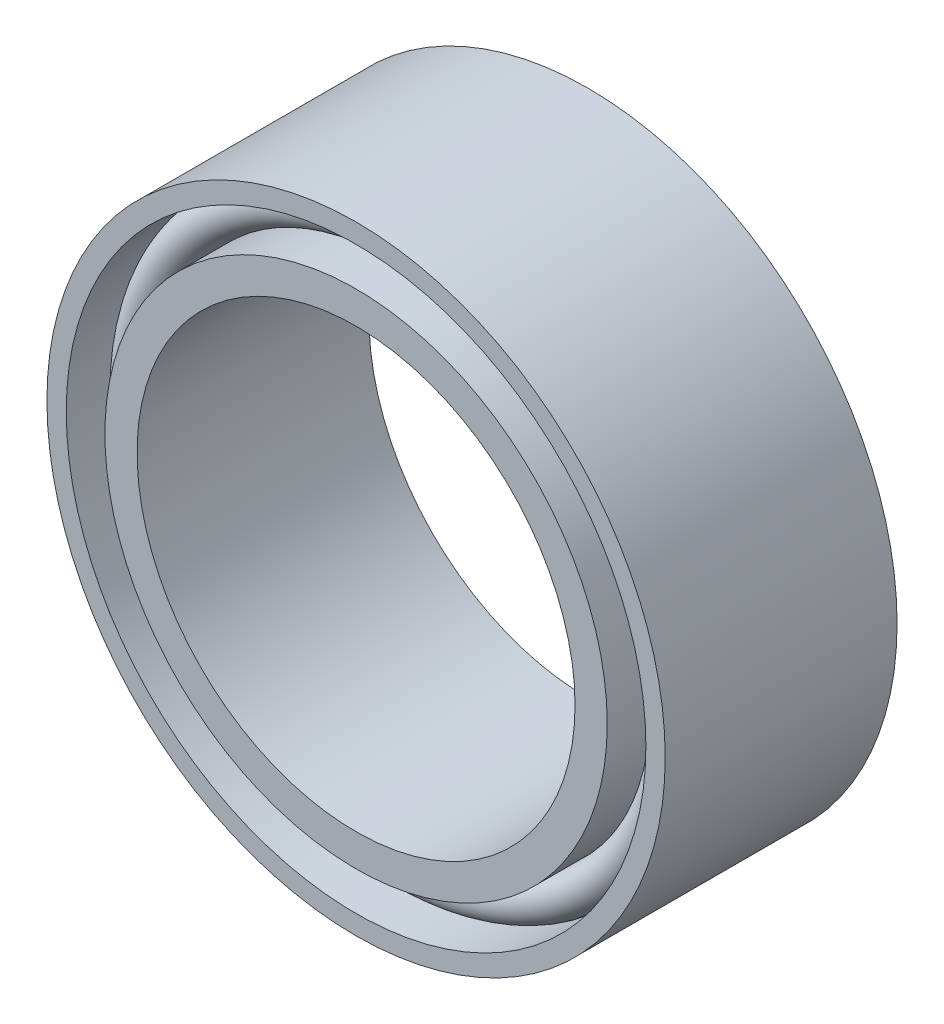
SolidWorks part; units mm, degrees
ref_plane "Ön Düzlem" through (0, 0, 0) normal (0, 0, 1) x (1, 0, 0)
ref_plane "Üst Düzlem" through (0, 0, 0) normal (0, 1, 0) x (1, 0, 0)
ref_plane "Sağ Düzlem" through (0, 0, 0) normal (1, 0, 0) x (0, 0, -1)
sketch "Çizim1" plane through (0, 0, 0) normal (0, 0, 1) x (1, 0, 0)
  circle A0 centre (0, 0) radius 24
  circle A1 centre (0, 0) radius 22.5
  dimension "D1" = 48
  dimension "D2" = 45
extrude "Yükseklik-Ekstrüzyon1" add sketch "Çizim1" along normal blind 18
sketch "Çizim2" plane through (0, 0, 18) normal (0, 0, 1) x (1, 0, 0)
  circle A0 centre (0, 0) radius 17
  circle A1 centre (0, 0) radius 19.5
  dimension "D1" = 34
  dimension "D2" = 39
extrude "Yükseklik-Ekstrüzyon2" add sketch "Çizim2" against normal blind 18 separate body
sketch "Çizim3" plane through (0, 0, 0) normal (1, 0, 0) x (0, 0, -1)
  line L0 (-14, 21) -> (-4, 21) construction
  line L1 (-14, 22.5) -> (-4, 22.5)
  line L2 (-14, 19.5) -> (-4, 19.5)
  line L3 (0, -24) -> (0, 24) construction
  arc A0 (-14, 22.5) -> (-14, 19.5) centre (-14, 21) ccw
  arc A1 (-4, 19.5) -> (-4, 22.5) centre (-4, 21) ccw
  point P2 (-9, 21)
  dimension "D1" = 3
  dimension "D2" = 10
  dimension "D3" = 4
  dimension "D4" = 22.5
revolve "Döndür1" add sketch "Çizim3" angle 360 about axis through (0, 0, 0) along (0, 0, 1)
